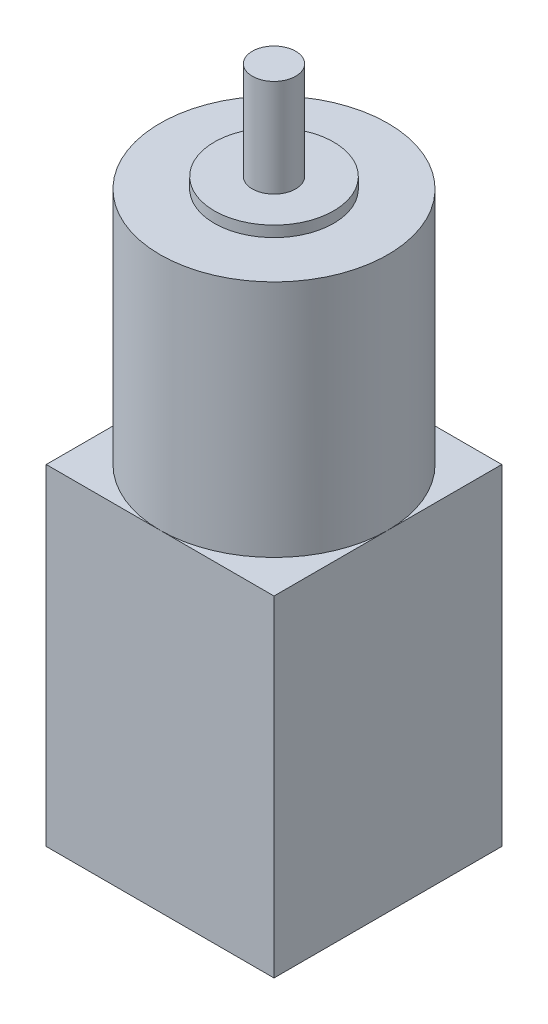
SolidWorks part; units mm, degrees
ref_plane "Front Plane" through (0, 0, 0) normal (0, 0, 1) x (1, 0, 0)
ref_plane "Top Plane" through (0, 0, 0) normal (0, 1, 0) x (1, 0, 0)
ref_plane "Right Plane" through (0, 0, 0) normal (1, 0, 0) x (0, 0, -1)
sketch "Sketch1" plane through (0, 0, 0) normal (0, 1, 0) x (1, 0, 0)
  line L1 (0, 0) -> (42, 0)
  line L2 (0, 0) -> (0, 42)
  line L3 (0, 42) -> (42, 42)
  line L4 (42, 0) -> (42, 42)
  dimension "D1" = 42
extrude "Boss-Extrude1" add sketch "Sketch1" along normal blind 61
sketch "Sketch2" plane through (0, 61, 0) normal (0, 1, 0) x (1, 0, 0)
  line L0 (0, 21) -> (42, 21) construction
  line L1 (0, 42) -> (0, 0) construction
  line L2 (42, 0) -> (42, 42) construction
  line L3 (21, 0) -> (21, 42) construction
  line L4 (0, 0) -> (42, 0) construction
  line L5 (42, 42) -> (0, 42) construction
  circle A0 centre (21, 21) radius 21
  dimension "D1" = 42
extrude "Boss-Extrude2" add sketch "Sketch2" along normal blind 44
sketch "Sketch3" plane through (0, 105, 0) normal (0, 1, 0) x (1, 0, 0)
  line L0 (0, 21) -> (42, 21) construction
  line L1 (21, 0) -> (21, 42) construction
  circle A0 centre (21, 21) radius 21 construction
  circle A1 centre (21, 21) radius 11
  dimension "D1" = 22
extrude "Boss-Extrude3" add sketch "Sketch3" along normal blind 2
sketch "Sketch4" plane through (0, 107, 0) normal (0, 1, 0) x (1, 0, 0)
  line L0 (10, 21) -> (32, 21) construction
  circle A0 centre (21, 21) radius 11 construction
  circle A1 centre (21, 21) radius 11 construction
  circle A2 centre (21, 21) radius 4
  dimension "D1" = 8
extrude "Boss-Extrude4" add sketch "Sketch4" along normal blind 18
